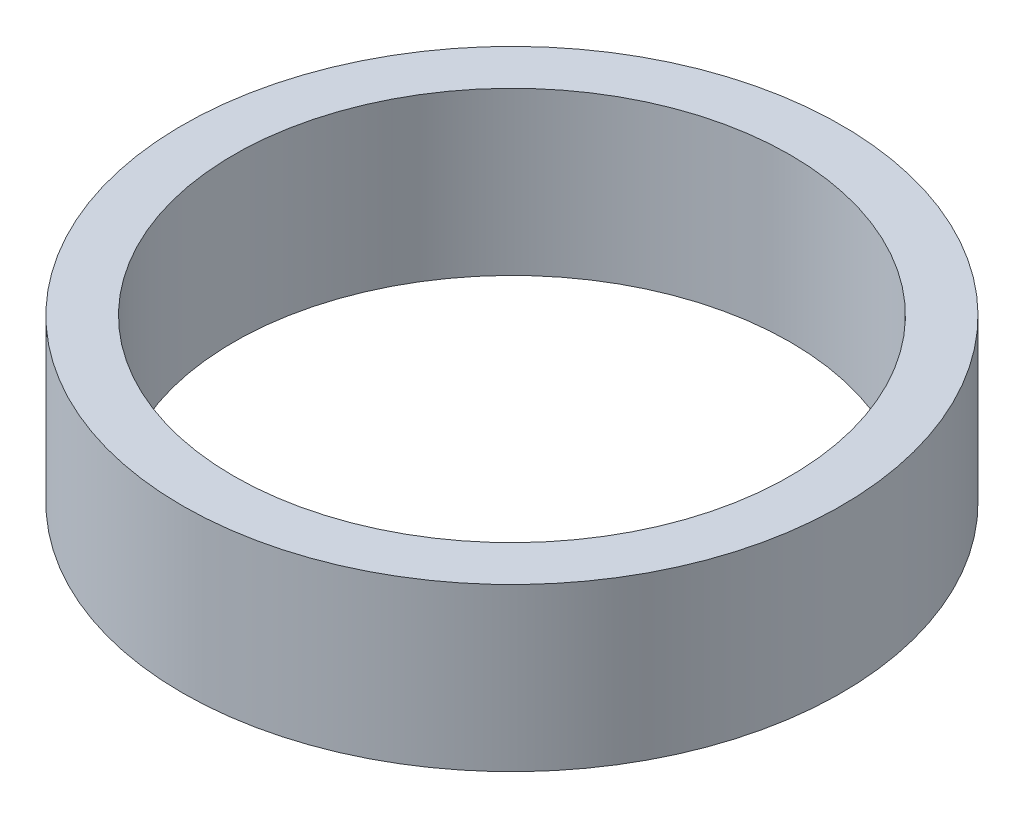
SolidWorks part; units mm, degrees
ref_plane "Front Plane" through (0, 0, 0) normal (0, 0, 1) x (1, 0, 0)
ref_plane "Top Plane" through (0, 0, 0) normal (0, 1, 0) x (1, 0, 0)
ref_plane "Right Plane" through (0, 0, 0) normal (1, 0, 0) x (0, 0, -1)
sketch "Sketch1" plane through (0, 0, 0) normal (0, 1, 0) x (1, 0, 0)
  circle A0 centre (0, 0) radius 6.1
  circle A1 centre (0, 0) radius 5.15
  dimension "D1" = 12.2
  dimension "D2" = 10.3
extrude "Boss-Extrude1" add sketch "Sketch1" along normal blind 3
